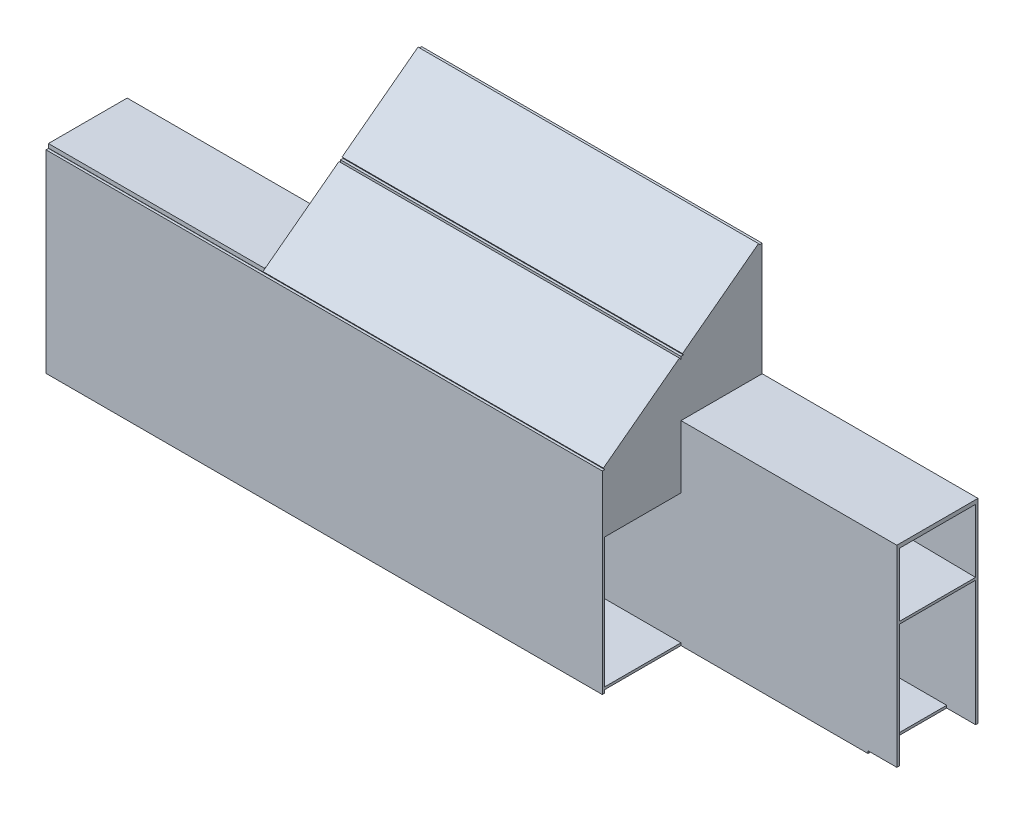
SolidWorks part; units mm, degrees
ref_plane "正面" through (0, 0, 0) normal (0, 0, 1) x (1, 0, 0)
ref_plane "平面" through (0, 0, 0) normal (0, 1, 0) x (1, 0, 0)
ref_plane "右側面" through (0, 0, 0) normal (1, 0, 0) x (0, 0, -1)
ref_plane "平面1" through (0, 0, 259) normal (0, 0, 1) x (1, 0, 0)
sketch "ｽｹｯﾁ2" plane through (0, 0, 259) normal (0, 0, 1) x (1, 0, 0)
  line L0 (0, 145) -> (2540, 145)
  line L1 (2540, 145) -> (2540, 778)
  line L2 (2540, 778) -> (1830, 778)
  line L3 (1830, 778) -> (1830, 961)
  line L4 (1830, 961) -> (710, 961)
  line L5 (710, 961) -> (710, 778)
  line L6 (710, 778) -> (0, 778)
  line L7 (0, 778) -> (0, 145)
extrude "ﾎﾞｽ - 押し出し1" add sketch "ｽｹｯﾁ2" along normal blind 8
ref_plane "平面2" through (0, 137, 0) normal (0, 1, 0) x (1, 0, 0)
sketch "ｽｹｯﾁ4" plane through (0, 137, 0) normal (0, 1, 0) x (1, 0, 0)
  line L0 (95, -259) -> (710, -259)
  line L1 (710, -259) -> (710, -8)
  line L2 (710, -8) -> (2445, -8)
  line L3 (2445, -8) -> (2445, -267)
  line L4 (2445, -267) -> (1830, -267)
  line L5 (1830, -267) -> (1830, -518)
  line L6 (1830, -518) -> (95, -518)
  line L7 (95, -518) -> (95, -259)
extrude "ﾎﾞｽ - 押し出し2" add sketch "ｽｹｯﾁ4" along normal blind 8
sketch "ｽｹｯﾁ5" plane through (0, 0, 0) normal (0, 0, 1) x (1, 0, 0)
  line L0 (710, 137) -> (2540, 137)
  line L1 (2540, 137) -> (2540, 778)
  line L2 (2540, 778) -> (1830, 778)
  line L3 (1830, 778) -> (1830, 1150)
  line L4 (1830, 1150) -> (710, 1150)
  line L5 (710, 1150) -> (710, 137)
extrude "ﾎﾞｽ - 押し出し3" add sketch "ｽｹｯﾁ5" along normal blind 8
ref_plane "平面3" through (0, 0, 518) normal (0, 0, 1) x (1, 0, 0)
sketch "ｽｹｯﾁ7" plane through (0, 0, 518) normal (0, 0, 1) x (1, 0, 0)
  line L0 (0, 127) -> (1830, 127)
  line L1 (1830, 127) -> (1830, 764)
  line L2 (1830, 764) -> (0, 764)
  line L3 (0, 764) -> (0, 127)
extrude "ﾎﾞｽ - 押し出し4" add sketch "ｽｹｯﾁ7" along normal blind 8
ref_plane "平面4" through (0, 0, 8) normal (0, 0, 1) x (1, 0, 0)
sketch "ｽｹｯﾁ9" plane through (0, 0, 8) normal (0, 0, 1) x (1, 0, 0)
  line L0 (710, 574.3249) -> (2540, 548.7543)
  line L1 (2540, 548.7543) -> (2540, 556.7543)
  line L2 (2540, 556.7543) -> (710, 582.3249)
  line L3 (710, 582.3249) -> (710, 574.3249)
extrude "ﾎﾞｽ - 押し出し5" add sketch "ｽｹｯﾁ9" along normal blind 251
ref_plane "平面5" through (0, 0, 267) normal (0, 0, 1) x (1, 0, 0)
sketch "ｽｹｯﾁ11" plane through (0, 0, 267) normal (0, 0, 1) x (1, 0, 0)
  line L0 (0, 548.7543) -> (1830, 574.3249)
  line L1 (1830, 574.3249) -> (1830, 582.3249)
  line L2 (1830, 582.3249) -> (0, 556.7543)
  line L3 (0, 556.7543) -> (0, 548.7543)
extrude "ﾎﾞｽ - 押し出し6" add sketch "ｽｹｯﾁ11" along normal blind 251
ref_plane "平面6" through (0, 765, 0) normal (0, 1, 0) x (1, 0, 0)
sketch "ｽｹｯﾁ13" plane through (0, 765, 0) normal (0, 1, 0) x (1, 0, 0)
  line L0 (0, -267) -> (710, -267)
  line L1 (710, -267) -> (710, -518)
  line L2 (710, -518) -> (0, -518)
  line L3 (0, -518) -> (0, -267)
  line L4 (1830, -8) -> (2540, -8)
  line L5 (2540, -8) -> (2540, -259)
  line L6 (2540, -259) -> (1830, -259)
  line L7 (1830, -259) -> (1830, -8)
extrude "ﾎﾞｽ - 押し出し7" add sketch "ｽｹｯﾁ13" along normal blind 13
ref_plane "平面7" through (710, 0, 0) normal (1, 0, 0) x (0, 0, -1)
sketch "ｽｹｯﾁ15" plane through (710, 0, 0) normal (1, 0, 0) x (0, 0, -1)
  line L0 (-8, 572) -> (-259, 572)
  line L1 (-259, 572) -> (-259, 961.3198)
  line L2 (-259, 961.3198) -> (-8, 1150.4619)
  line L3 (-8, 1150.4619) -> (-8, 572)
  line L4 (-267, 572) -> (-518, 572)
  line L5 (-518, 572) -> (-518, 763.6451)
  line L6 (-518, 763.6451) -> (-267, 952.7871)
  line L7 (-267, 952.7871) -> (-267, 572)
extrude "ﾎﾞｽ - 押し出し8" add sketch "ｽｹｯﾁ15" along normal blind 10
ref_plane "平面8" through (1820, 0, 0) normal (1, 0, 0) x (0, 0, -1)
sketch "ｽｹｯﾁ17" plane through (1820, 0, 0) normal (1, 0, 0) x (0, 0, -1)
  line L0 (-8, 572) -> (-259, 572)
  line L1 (-259, 572) -> (-259, 961.3198)
  line L2 (-259, 961.3198) -> (-8, 1150.4619)
  line L3 (-8, 1150.4619) -> (-8, 572)
  line L4 (-267, 572) -> (-518, 572)
  line L5 (-518, 572) -> (-518, 763.6451)
  line L6 (-518, 763.6451) -> (-267, 952.7871)
  line L7 (-267, 952.7871) -> (-267, 572)
extrude "ﾎﾞｽ - 押し出し9" add sketch "ｽｹｯﾁ17" along normal blind 10
sketch "ｽｹｯﾁ18" plane through (710, 0, 0) normal (1, 0, 0) x (0, 0, -1)
  line L0 (-12.14, 1154.855) -> (-262.14, 966.4665)
  line L1 (-262.14, 966.4665) -> (-258.5291, 961.6747)
  line L2 (-258.5291, 961.6747) -> (-8.5291, 1150.0632)
  line L3 (-8.5291, 1150.0632) -> (-12.14, 1154.855)
extrude "ﾎﾞｽ - 押し出し10" add sketch "ｽｹｯﾁ18" along normal blind 1120
sketch "ｽｹｯﾁ19" plane through (710, 0, 0) normal (1, 0, 0) x (0, 0, -1)
  line L0 (-272.34, 958.7802) -> (-522.34, 770.3917)
  line L1 (-522.34, 770.3917) -> (-517.5255, 764.0026)
  line L2 (-517.5255, 764.0026) -> (-267.5255, 952.3912)
  line L3 (-267.5255, 952.3912) -> (-272.34, 958.7802)
extrude "ﾎﾞｽ - 押し出し11" add sketch "ｽｹｯﾁ19" along normal blind 1120
